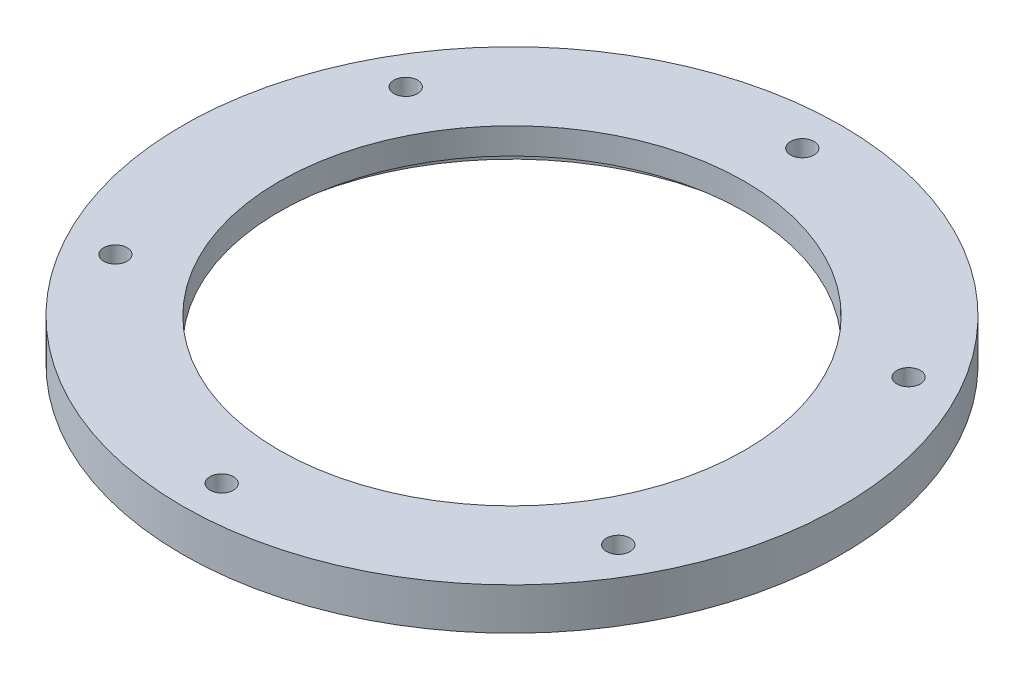
SolidWorks part; units mm, degrees
material "ABS"
ref_plane "Front" through (0, 0, 0) normal (0, 0, 1) x (1, 0, 0)
ref_plane "Top" through (0, 0, 0) normal (0, 1, 0) x (1, 0, 0)
ref_plane "Right" through (0, 0, 0) normal (1, 0, 0) x (0, 0, -1)
sketch "Croquis1" plane through (0, 0, 0) normal (0, 1, 0) x (1, 0, 0)
  line L0 (0, -8.25) -> (0, 8.25) construction
  line L1 (-8.25, 0) -> (8.25, 0) construction
  circle A0 centre (0, 0) radius 63
  circle A1 centre (0, 0) radius 44.5
  circle A2 centre (0, 55.5) radius 2.25
  circle A3 centre (48.0644, 27.75) radius 2.25
  circle A4 centre (48.0644, -27.75) radius 2.25
  circle A5 centre (0, -55.5) radius 2.25
  circle A6 centre (-48.0644, -27.75) radius 2.25
  circle A7 centre (-48.0644, 27.75) radius 2.25
  dimension "D1" = 126
  dimension "D2" = 89
  dimension "D4" = 4.5
  dimension "D3" = 55.5
  dimension "D5" = 6
extrude "Saliente-Extruir1" add sketch "Croquis1" along normal blind 8
sketch "Croquis2" plane through (0, 0, 0) normal (0, -1, 0) x (1, 0, 0)
  circle A0 centre (0, 0) radius 48
  dimension "D1" = 96
extrude "Cortar-Extruir1" cut sketch "Croquis2" against normal blind 3
